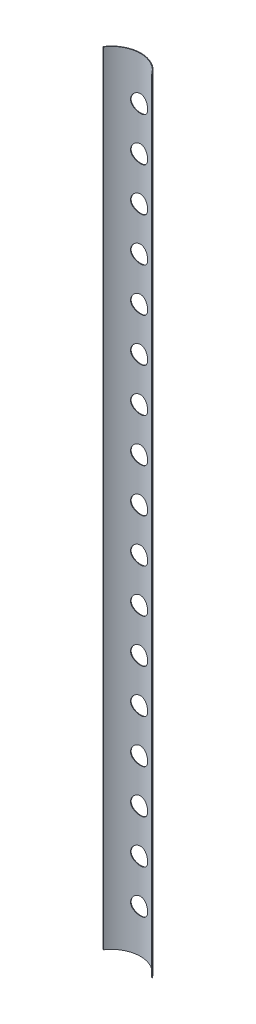
SolidWorks part; units mm, degrees
ref_plane "Front Plane" through (0, 0, 0) normal (0, 0, 1) x (1, 0, 0)
ref_plane "Top Plane" through (0, 0, 0) normal (0, 1, 0) x (1, 0, 0)
ref_plane "Right Plane" through (0, 0, 0) normal (1, 0, 0) x (0, 0, -1)
sketch "Sketch2" plane through (0, 0, 0) normal (0, 1, 0) x (1, 0, 0)
  line L2 (-18.3917, -0.1313) -> (-18.0217, -0.1313)
  line L3 (10.0773, -0.1313) -> (10.4983, -0.1313)
  arc A0 (-18.3917, -0.1313) -> (10.4983, -0.1313) centre (-3.9467, -9.5626) cw
  arc A1 (-18.0217, -0.1313) -> (10.0773, -0.1313) centre (-3.9722, -9.5455) cw
  dimension "D2" = 28.89
  dimension "D3" = 0.37
  dimension "D1" = 0.37
extrude "Boss-Extrude1" add sketch "Sketch2" along normal blind 457.2
ref_plane "Plane1" through (-18.3917, 0, 0.1313) normal (0, -1, 0) x (-1, 0, 0)
sketch "Sketch4" plane through (0, 0, 0.1313) normal (0, 0, 1) x (1, 0, 0)
  circle A1 centre (-3.9467, 25.4) radius 5
  dimension "D2" = 10
extrude "Cut-Extrude2" cut sketch "Sketch4" against normal blind 25.4
pattern_linear "LPattern1" count 17 spacing 25.4 along (0, 1, 0) of "Cut-Extrude2"
